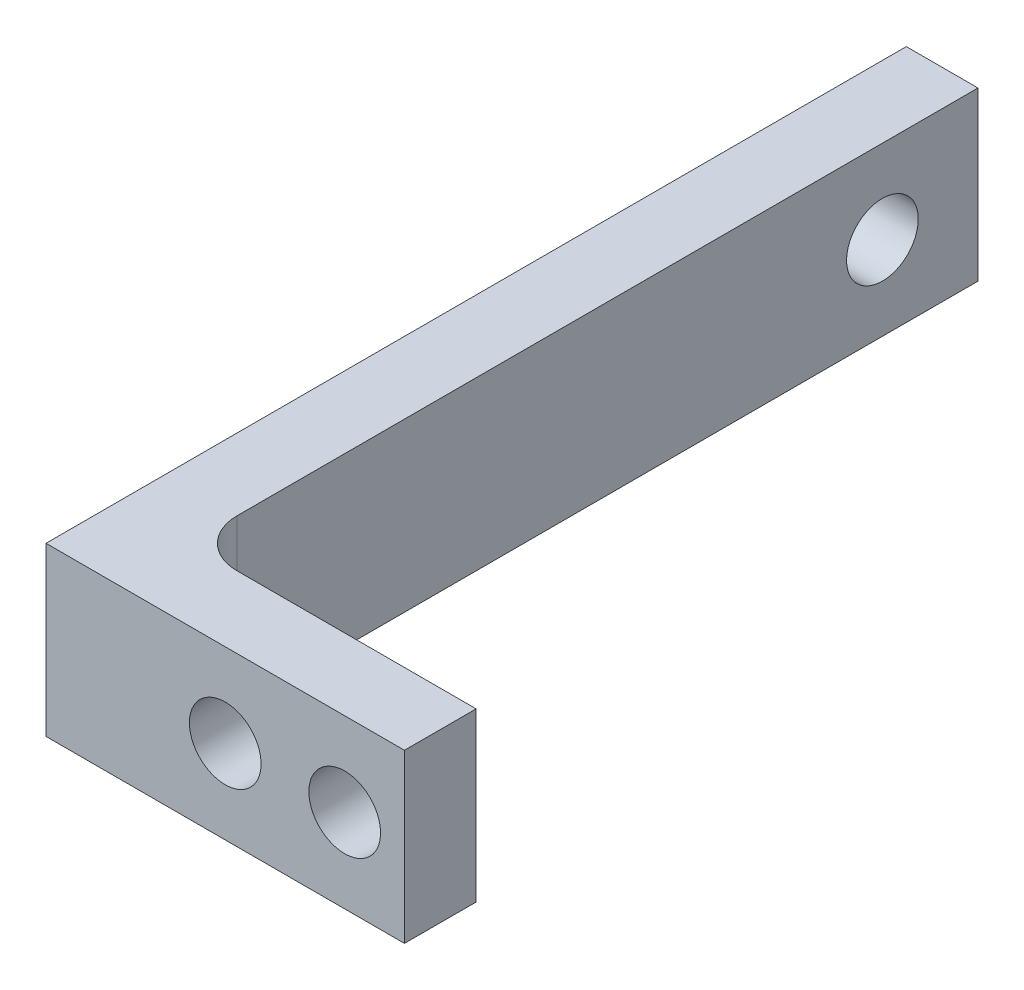
SolidWorks part; units mm, degrees
ref_plane "Front Plane" through (0, 0, 0) normal (0, 0, 1) x (1, 0, 0)
ref_plane "Top Plane" through (0, 0, 0) normal (0, 1, 0) x (1, 0, 0)
ref_plane "Right Plane" through (0, 0, 0) normal (1, 0, 0) x (0, 0, -1)
sketch "Sketch1" plane through (0, 0, 0) normal (0, 1, 0) x (1, 0, 0)
  line L1 (0, 0) -> (10, 0)
  line L2 (0, 0) -> (0, 3)
  line L3 (0, 3) -> (10, 3)
  line L4 (10, 0) -> (10, 3)
  line L5 (0, 0) -> (3, 0)
  line L6 (0, 0) -> (0, 36)
  line L7 (0, 36) -> (3, 36)
  line L8 (3, 0) -> (3, 36)
  dimension "D1" = 3
  dimension "D2" = 10
  dimension "D3" = 3
  dimension "D4" = 36
extrude "Boss-Extrude1" add sketch "Sketch1" along normal blind 7 contours L3 L8 L7 L6 | L1 L8 L3 L2
fillet "Fillet1" radius 2 1 edges at (3, 3.5, -3)
sketch "Sketch2" plane through (0, 0, -3) normal (0, 0, -1) x (-1, 0, 0)
  line L0 (-5, 7) -> (-10, 7) construction
  line L1 (-5, 0) -> (-5, 7) construction
  circle A0 centre (-7.5, 3.5) radius 1.5
  dimension "D1" = 3
  dimension "D2" = 3.5
  dimension "D3" = 2.5
extrude "Cut-Extrude1" cut sketch "Sketch2" against normal blind 7
sketch "Sketch3" plane through (0, 0, 0) normal (0, 0, 1) x (1, 0, 0)
  line L2 (10, 7) -> (15, 7)
  line L3 (10, 7) -> (10, 0)
  line L4 (10, 0) -> (15, 0)
  line L5 (15, 7) -> (15, 0)
  dimension "D1" = 5
  dimension "D2" = 7
extrude "Boss-Extrude2" add sketch "Sketch3" against normal blind 3
sketch "Sketch4" plane through (0, 0, -3) normal (0, 0, -1) x (-1, 0, 0)
  line L0 (-5, 7) -> (-15, 7) construction
  line L1 (-15, 0) -> (-15, 7) construction
  circle A0 centre (-12.5, 3.5) radius 1.5
  dimension "D1" = 3
  dimension "D2" = 3.5
  dimension "D3" = 2.5
extrude "Cut-Extrude2" cut sketch "Sketch4" against normal blind 3
sketch "Sketch5" plane through (0, 0, 0) normal (-1, 0, 0) x (0, 0, 1)
  line L0 (0, 7) -> (-36, 7) construction
  line L1 (-36, 7) -> (-36, 0) construction
  circle A0 centre (-32, 3.5) radius 1.5
  dimension "D1" = 3
  dimension "D2" = 3.5
  dimension "D3" = 4
extrude "Cut-Extrude3" cut sketch "Sketch5" against normal blind 3
